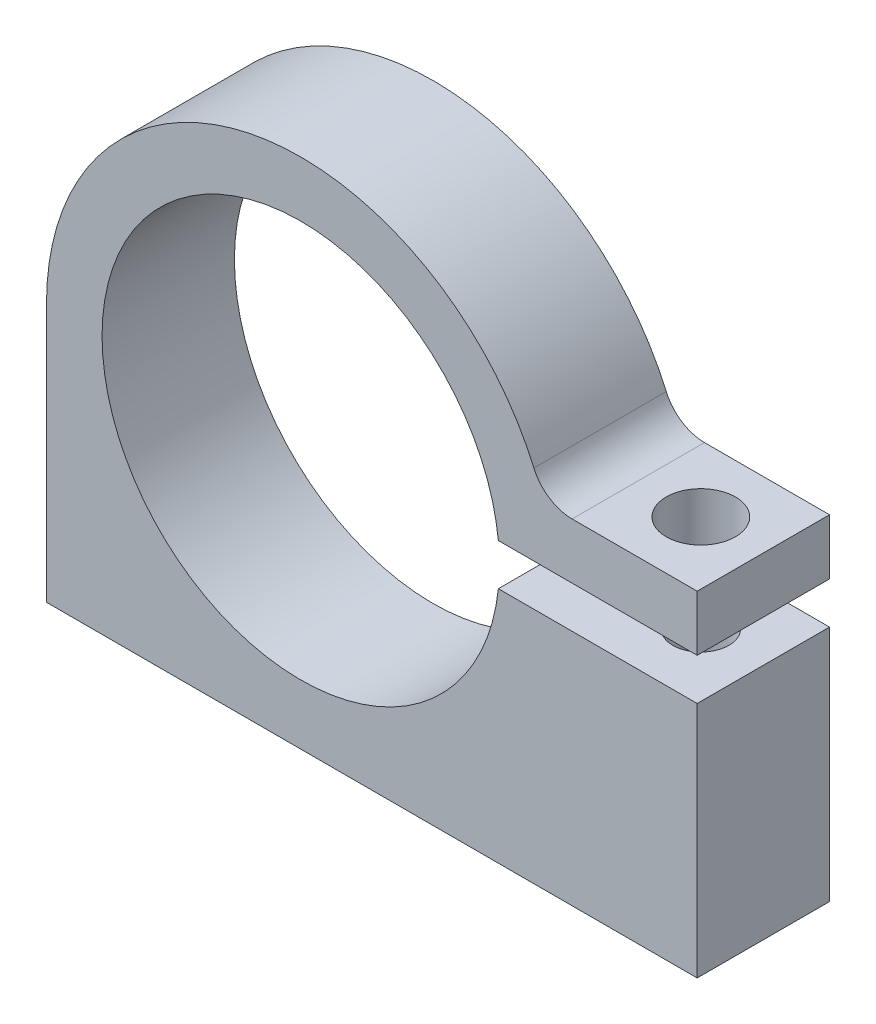
SolidWorks part; units mm, degrees
material "6061-T6 (SS)"
ref_plane "Front" through (0, 0, 0) normal (0, 0, 1) x (1, 0, 0)
ref_plane "Top" through (0, 0, 0) normal (0, 1, 0) x (1, 0, 0)
ref_plane "Right" through (0, 0, 0) normal (1, 0, 0) x (0, 0, -1)
sketch "Sketch1" plane through (0, 0, 0) normal (0, 0, 1) x (1, 0, 0)
  line L0 (14.2211, 1.5) -> (28.5305, 1.5)
  line L1 (28.5305, 1.5) -> (28.5305, 5.5)
  line L2 (28.5305, 5.5) -> (19.5305, 5.5)
  line L3 (-18.3, 0) -> (-18.3, -18.61)
  line L4 (-18.3, -18.61) -> (28.5305, -18.61)
  line L5 (14.3, 0) -> (33.7624, 0) construction
  line L6 (14.2211, -1.5) -> (28.5305, -1.5)
  line L7 (28.5305, -1.5) -> (28.5305, -18.61)
  circle A0 centre (0, 0) radius 14 construction
  circle A1 centre (0, 0) radius 14.3
  arc A2 (16.7797, 7.3028) -> (-18.3, 0) centre (0, 0) ccw
  arc A3 (19.5305, 5.5) -> (16.7797, 7.3028) centre (19.5305, 8.5) cw
  dimension "D1" = 28
  dimension "D3" = 18.61
  dimension "D4" = 4
  dimension "D7" = 3
  dimension "D5" = 3
  dimension "D6" = 4
  dimension "D8" = 9
  dimension "D2" = 0.3
extrude "Boss-Extrude1" add sketch "Sketch1" along normal blind 9.525 contours L2 A2 L3 L4 L7 L6 A1 L0 L1
hole_wizard "#10 Clearance Hole1" positions "Sketch2" profile "Sketch3" hole size "#10" standard "ANSI Inch"
sketch "Sketch2" plane through (0, 5.5, 0) normal (0, 1, 0) x (1, 0, 0)
  line L0 (19.5305, -9.525) -> (28.5305, 0) construction
  point P7 (24.0305, -4.7625)
sketch "Sketch3" plane through (24.0305, 5.5, 4.7625) normal (1, 0, 0) x (0, 0, 1)
  line L0 (0, 0) -> (0, 5.4957)
  line L1 (0, 5.4957) -> (2.4892, 4)
  line L2 (2.4892, 4) -> (2.4892, 0)
  line L5 (2.4892, 0) -> (0, 0)
  line L10 (0, 5.4957) -> (-2.4892, 4) construction
  line L11 (0, -6.35) -> (0, 107.95) construction
  dimension "Hole Dia." = 4.9784
  dimension "Hole Depth" = 4
  dimension "Drill Angle" = 118
hole_wizard "#10-32 Tapped Hole1" positions "Sketch4" profile "Sketch6" tap size "#10-32" standard "ANSI Inch" end condition through all
sketch "Sketch4" plane through (0, -1.5, 0) normal (0, 1, 0) x (1, 0, 0)
  point P0 (24.0305, -4.7625)
sketch "Sketch6" plane through (24.0305, -1.5, 4.7625) normal (1, 0, 0) x (0, 0, 1)
  line L0 (0, 0) -> (0, 17.11)
  line L1 (0, 17.11) -> (2.0193, 17.11)
  line L2 (2.0193, 17.11) -> (2.0193, 0)
  line L5 (2.0193, 0) -> (0, 0)
  line L11 (0, -6.35) -> (0, 107.95) construction
  dimension "Thru Tap Drill Dia." = 4.0386
  dimension "Thru Tap Drill Depth" = 17.11
cosmetic thread "Hole Thread1" parameters "D2"=4.826
hole_wizard "#10-32 Tapped Hole2" positions "Sketch7" profile "Sketch8" tap size "#10-32" standard "ANSI Inch"
sketch "Sketch7" plane through (0, -18.61, 0) normal (0, -1, 0) x (-1, 0, 0)
  line L0 (18.3, -4.7625) -> (12.9695, -4.7625) construction
  line L1 (18.3, -9.525) -> (18.3, 0) construction
  circle A0 centre (-24.0305, -4.7625) radius 2.0193 construction
  point P0 (12.9695, -4.7625)
  dimension "D1" = 37
cosmetic thread "Hole Thread2" parameters "D2"=4.826
sketch "Sketch8" plane through (-12.9695, -18.61, 4.7625) normal (1, 0, 0) x (0, 0, -1)
  line L0 (0, 0) -> (0, 8.2133)
  line L1 (0, 8.2133) -> (2.0193, 7)
  line L2 (2.0193, 7) -> (2.0193, 0)
  line L5 (2.0193, 0) -> (0, 0)
  line L10 (0, 8.2133) -> (-2.0193, 7) construction
  line L11 (0, -6.35) -> (0, 107.95) construction
  dimension "Tap Drill Dia." = 4.0386
  dimension "Tap Drill Depth" = 7
  dimension "Drill Angle" = 118
